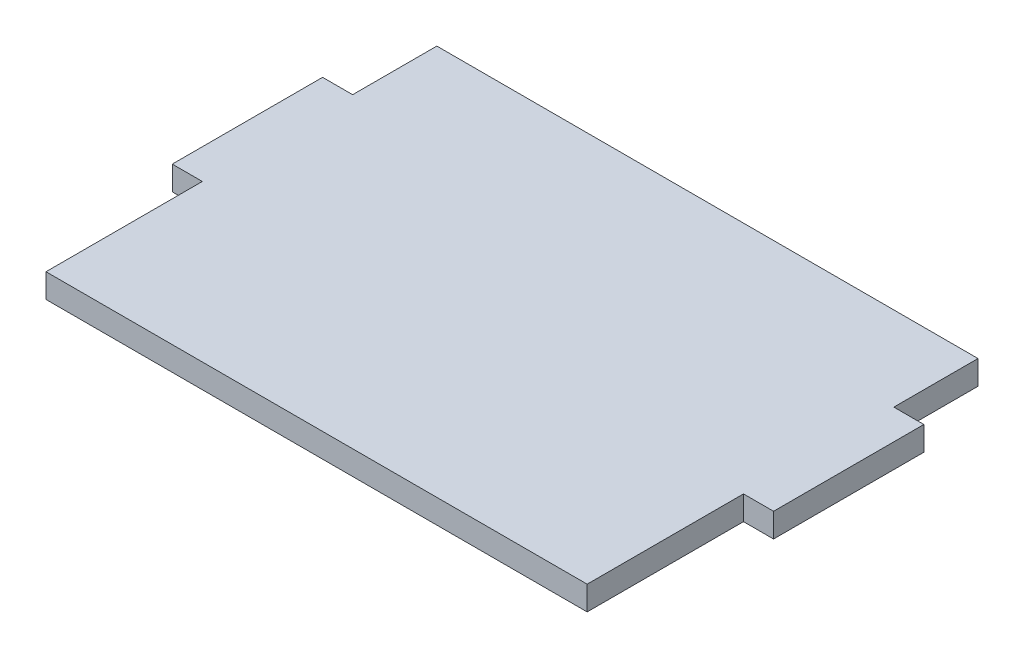
SolidWorks part; units mm, degrees
ref_plane "Alzado" through (0, 0, 0) normal (0, 0, 1) x (1, 0, 0)
ref_plane "Planta" through (0, 0, 0) normal (0, 1, 0) x (1, 0, 0)
ref_plane "Vista lateral" through (0, 0, 0) normal (1, 0, 0) x (0, 0, -1)
sketch "Croquis1" plane through (0, 0, 0) normal (0, 1, 0) x (1, 0, 0)
  line L1 (-45, -32.5) -> (45, -32.5)
  line L2 (-50, -6.5) -> (-50, 18.5)
  line L3 (-45, 32.5) -> (45, 32.5)
  line L4 (50, -6.5) -> (50, 18.5)
  line L5 (-45, -29.25) -> (45, 29.25) construction
  line L6 (-45, 29.25) -> (45, -29.25) construction
  line L13 (-50, 18.5) -> (-45, 18.5)
  line L14 (-45, 32.5) -> (-45, 18.5)
  line L17 (-50, -6.5) -> (-45, -6.5)
  line L18 (-45, -32.5) -> (-45, -6.5)
  line L21 (50, 18.5) -> (45, 18.5)
  line L22 (45, 32.5) -> (45, 18.5)
  line L25 (50, -6.5) -> (45, -6.5)
  line L26 (45, -32.5) -> (45, -6.5)
  point P0 (0, 0)
  dimension "D3" = 14
  dimension "D4" = 5
  dimension "D5" = 5
  dimension "D6" = 26
  dimension "D7" = 14
  dimension "D8" = 5
  dimension "D9" = 5
  dimension "D10" = 26
extrude "Saliente-Extruir1" add sketch "Croquis1" along normal blind 4
